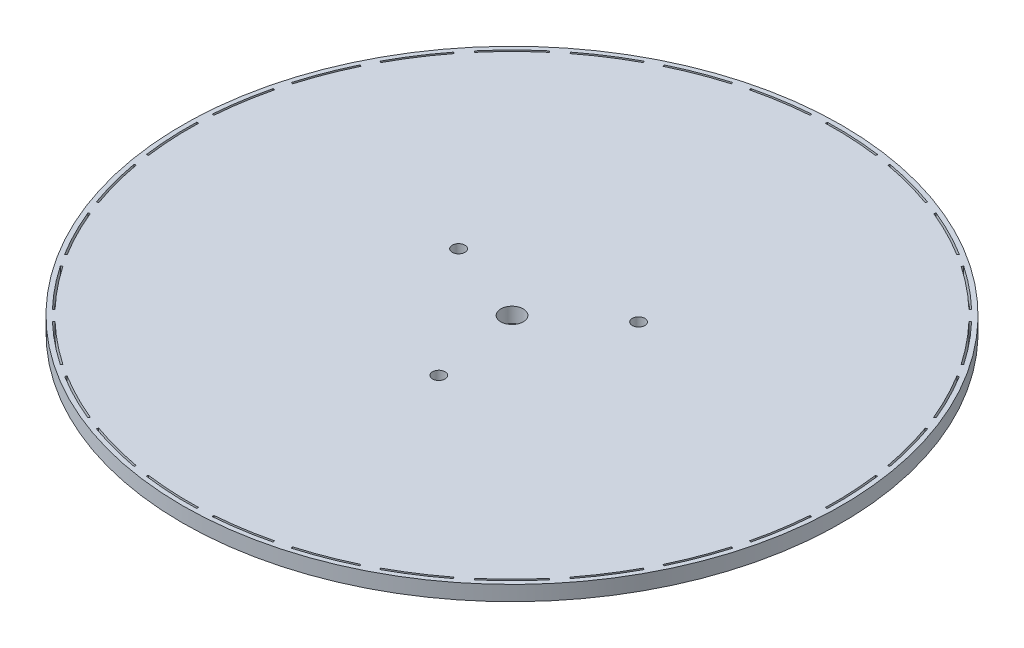
SolidWorks part; units mm, degrees
ref_plane "Front Plane" through (0, 0, 0) normal (0, 0, 1) x (1, 0, 0)
ref_plane "Top Plane" through (0, 0, 0) normal (0, 1, 0) x (1, 0, 0)
ref_plane "Right Plane" through (0, 0, 0) normal (1, 0, 0) x (0, 0, -1)
sketch "Sketch5" plane through (0, 0, 0) normal (0, 1, 0) x (1, 0, 0)
  circle A0 centre (0, 0) radius 139.7
  dimension "D1" = 279.4
extrude "Boss-Extrude2" add sketch "Sketch5" along normal blind 6.35
sketch "Sketch7" plane through (0, 6.35, 0) normal (0, 1, 0) x (1, 0, 0)
  line L0 (128.9901, 46.1617) -> (129.7374, 46.4291)
  line L1 (134.7982, 24.4704) -> (135.5791, 24.6122)
  circle A0 centre (0, 0) radius 137.795
  circle A1 centre (0, 0) radius 137.0012
  arc A2 (129.7374, 46.4291) -> (135.5791, 24.6122) centre (0, 0) cw
  arc A3 (129.0528, 45.9861) -> (134.7982, 24.4704) centre (0, 0) cw
  arc A4 (129.7374, 46.4291) -> (135.5791, 24.6122) centre (0, 0) cw
  dimension "D1" = 275.59
  dimension "D2" = 274.0025
extrude "Cut-Extrude1" cut sketch "Sketch7" against normal blind 6.35 contours A1 L1 A0 L0
pattern_circular "CirPattern1" count 30 over 360 about axis through (0, 0, 0) along (0, 1, 0) of "Cut-Extrude1"
sketch "Sketch9" plane through (0, 6.35, 0) normal (0, 1, 0) x (1, 0, 0)
  line L1 (6.516, -37.5387) -> (29.2514, 24.4124) construction
  line L2 (29.2514, 24.4124) -> (-35.7674, 13.1263) construction
  line L3 (-35.7674, 13.1263) -> (6.516, -37.5387) construction
  circle A0 centre (0, 0) radius 19.05 construction
  circle A1 centre (29.2514, 24.4124) radius 2.667
  circle A2 centre (6.516, -37.5387) radius 2.667
  circle A3 centre (-35.7674, 13.1263) radius 2.667
  dimension "D1" = 5.334
  dimension "D2" = 38.1
  dimension "D3" = 108.4821
extrude "Cut-Extrude3" cut sketch "Sketch9" against normal blind 6.35
sketch "Sketch10" plane through (0, 6.35, 0) normal (0, 1, 0) x (1, 0, 0)
  circle A0 centre (0, 0) radius 4.7625
  dimension "D1" = 9.525
extrude "Cut-Extrude4" cut sketch "Sketch10" against normal blind 6.35
